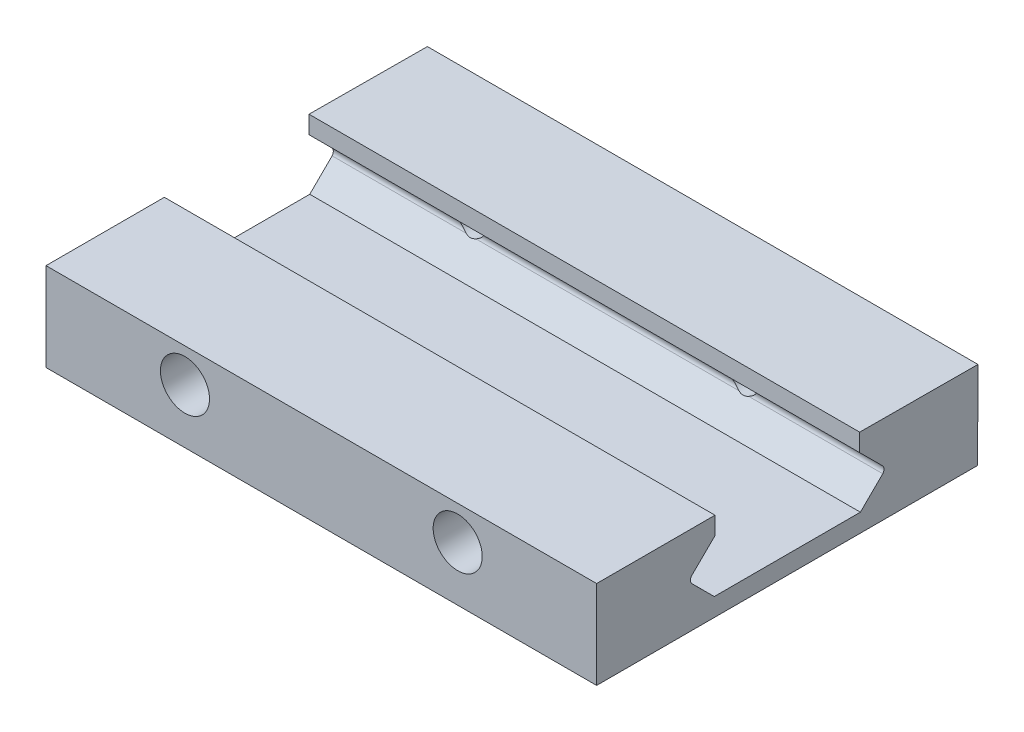
SolidWorks part; units mm, degrees
ref_plane "Front Plane" through (0, 0, 0) normal (0, 0, 1) x (1, 0, 0)
ref_plane "Top Plane" through (0, 0, 0) normal (0, 1, 0) x (1, 0, 0)
ref_plane "Right Plane" through (0, 0, 0) normal (1, 0, 0) x (0, 0, -1)
sketch "Sketch1" plane through (0, 0, 0) normal (0, 1, 0) x (1, 0, 0)
  line L0 (30.6755, 22.2138) -> (-29.8908, 22.2138) construction
  line L5 (-29.8908, -19.6962) -> (30.6755, -19.6962)
  line L6 (-29.8908, -19.6962) -> (-29.8908, 22.2138)
  line L7 (-29.8908, 22.2138) -> (30.6755, 22.2138)
  line L8 (30.6755, -19.6962) -> (30.6755, 22.2138)
extrude "Boss-Extrude1" add sketch "Sketch1" along normal blind 2
ref_plane "Plane1" through (-29.8908, 2, 19.6962) normal (-1, 0, 0) x (0, 0, 1)
ref_plane "Plane2" through (-29.8908, 0, 0) normal (-1, 0, 0) x (0, 0, 1)
sketch "Sketch4" plane through (-29.8908, 0, 0) normal (-1, 0, 0) x (0, 0, 1)
  line L0 (19.6962, 2) -> (19.6962, 9.7083)
  line L1 (29.2808, 9.7083) -> (16.7408, 9.7083) construction
  line L2 (19.6962, 9.7083) -> (6.5766, 9.7083)
  line L3 (-9.2743, 1.9598) -> (-22.2138, 1.9598)
  line L5 (6.6766, 9.7083) -> (6.6766, 7.7631)
  line L6 (6.5766, 9.7083) -> (6.5766, 7.7213) construction
  line L7 (6.6766, 7.7631) -> (9.2602, 5.2124)
  line L8 (6.7568, 2) -> (9.2459, 4.483)
  line L9 (6.7568, 2) -> (19.6962, 2)
  line L11 (6.5766, 7.7213) -> (9.1112, 5.219) construction
  line L12 (-22.2138, 2) -> (19.6962, 2) construction
  line L13 (9.1121, 4.4908) -> (6.6152, 2) construction
  line L14 (-1.2781, 9.7083) -> (-1.2588, 2) construction
  line L15 (-9.1328, 9.7083) -> (6.5766, 9.7083) construction
  line L17 (-9.2743, 1.9598) -> (-11.7757, 4.4302)
  line L18 (-9.2229, 7.7232) -> (-11.7938, 5.1596)
  line L19 (-9.2327, 9.6684) -> (-9.2229, 7.7232)
  line L20 (-22.2522, 9.6031) -> (-9.2327, 9.6684)
  line L21 (-22.2135, 1.8949) -> (-22.2522, 9.6031)
  arc A0 (9.2459, 4.483) -> (9.2602, 5.2124) centre (8.7543, 4.8575) ccw
  arc A1 (9.1877, 4.5926) -> (9.1112, 5.219) centre (8.7543, 4.8575) ccw construction
  arc A2 (-11.7757, 4.4302) -> (-11.7938, 5.1596) centre (-11.2861, 4.8072) cw
  dimension "D2" = 0.11
  dimension "D1" = 0.1
  dimension "D3" = 0.1
  dimension "D4" = 0.1
extrude "Boss-Extrude2" add sketch "Sketch4" against normal up to surface (60.5663 mm away) contours L17 A2 L18 L19 L20 L21 L3 | A0 L8 L9 L0 L2 L5 L7 up to face at (30.6755, 1, -1.2588)
sketch "Sketch5" plane through (0, -0.1114, -22.2034) normal (0, -0.005, -1) x (-1, 0, 0)
  line L0 (-0.3923, 9.7146) -> (-0.3923, 2.0712) construction
  line L1 (-30.6755, 9.7146) -> (29.8908, 9.7146) construction
  line L2 (-30.6755, 2.0712) -> (29.8908, 2.0712) construction
  circle A0 centre (14.6077, 5.8929) radius 1.5
  circle A1 centre (-15.3923, 5.8929) radius 1.5
  dimension "D2" = 3
  dimension "D1" = 15
extrude "Cut-Extrude1" cut sketch "Sketch5" against normal up to surface (41.9373 mm away)
sketch "Sketch6" plane through (0, -0.1114, -22.2034) normal (0, -0.005, -1) x (-1, 0, 0)
  circle A0 centre (14.6077, 5.8929) radius 2.7
  circle A1 centre (-15.3923, 5.8929) radius 2.7
  dimension "D1" = 5.4
  dimension "D2" = 5.4
extrude "Cut-Extrude2" cut sketch "Sketch6" against normal blind 4.1
sketch "Sketch9" plane through (0, 0, 19.6962) normal (0, 0, 1) x (1, 0, 0)
  circle A0 centre (15.3923, 5.9918) radius 2.7
  circle A1 centre (-14.6077, 5.9918) radius 2.7
  dimension "D1" = 5.4
  dimension "D2" = 5.4
extrude "Cut-Extrude3" cut sketch "Sketch9" against normal blind 4.1
